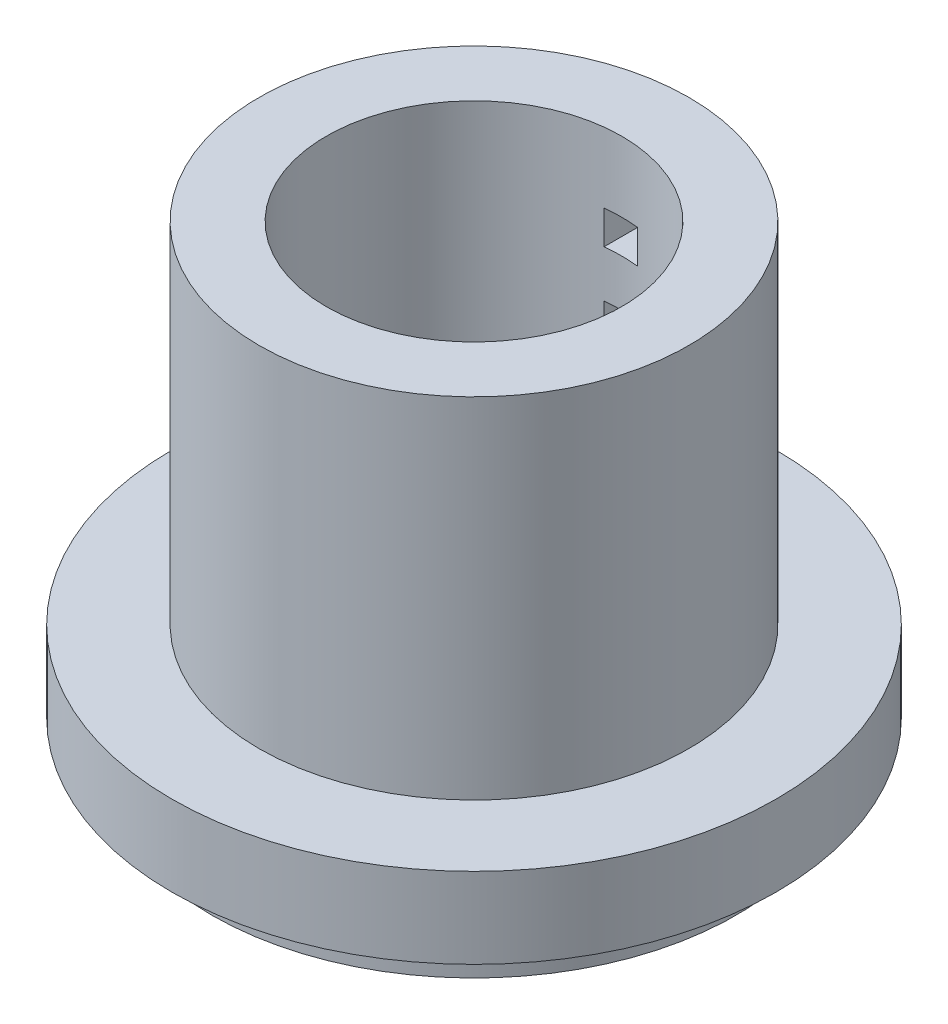
SolidWorks part; units mm, degrees
ref_plane "Front Plane" through (0, 0, 0) normal (0, 0, 1) x (1, 0, 0)
ref_plane "Top Plane" through (0, 0, 0) normal (0, 1, 0) x (1, 0, 0)
ref_plane "Right Plane" through (0, 0, 0) normal (1, 0, 0) x (0, 0, -1)
sketch "Sketch2" plane through (0, 0, 0) normal (0, 0, 1) x (1, 0, 0)
  line L0 (11, 0) -> (17.5, 0)
  line L1 (17.5, 0) -> (17.5, -3)
  line L2 (17.5, -3) -> (19.5, -3)
  line L3 (19.5, -3) -> (19.5, 0)
  line L4 (19.5, 0) -> (22.5, 0)
  line L5 (22.5, 0) -> (22.5, 6)
  line L6 (22.5, 6) -> (16, 6)
  line L7 (16, 6) -> (16, 32)
  line L8 (16, 32) -> (11, 32)
  line L10 (11, 32) -> (11, 6)
  line L11 (11, 6) -> (11, 0)
revolve "Revolve1" add sketch "Sketch2" angle 360 about L0
sketch "Sketch4" plane through (0, 0, 0) normal (0, 0, 1) x (1, 0, 0)
  line L0 (0, -4.8224) -> (0, 32) construction
  line L1 (16, 32) -> (-16, 32) construction
  line L3 (-1.25, 14.7724) -> (1.25, 14.7724)
  line L4 (-1.25, 14.7724) -> (-1.25, 12.2724)
  line L5 (-1.25, 8.7724) -> (1.25, 8.7724)
  line L6 (-1.25, 8.7724) -> (-1.25, 6.2724)
  line L7 (-1.25, 6.2724) -> (1.25, 6.2724)
  line L8 (1.25, 8.7724) -> (1.25, 6.2724)
  line L9 (-1.25, 8.7724) -> (1.25, 6.2724) construction
  line L10 (-1.25, 6.2724) -> (1.25, 8.7724) construction
  line L11 (-1.25, 12.2724) -> (1.25, 12.2724)
  line L12 (1.25, 14.7724) -> (1.25, 12.2724)
  line L13 (-1.25, 20.7724) -> (1.25, 20.7724)
  line L14 (-1.25, 20.7724) -> (-1.25, 18.2724)
  line L15 (-1.25, 18.2724) -> (1.25, 18.2724)
  line L16 (1.25, 20.7724) -> (1.25, 18.2724)
  line L17 (-1.25, 26.7724) -> (1.25, 26.7724)
  line L18 (-1.25, 26.7724) -> (-1.25, 24.2724)
  line L19 (-1.25, 24.2724) -> (1.25, 24.2724)
  line L20 (1.25, 26.7724) -> (1.25, 24.2724)
  dimension "D1" = 4
extrude "Cut-Extrude1" cut sketch "Sketch4" against normal blind 20
